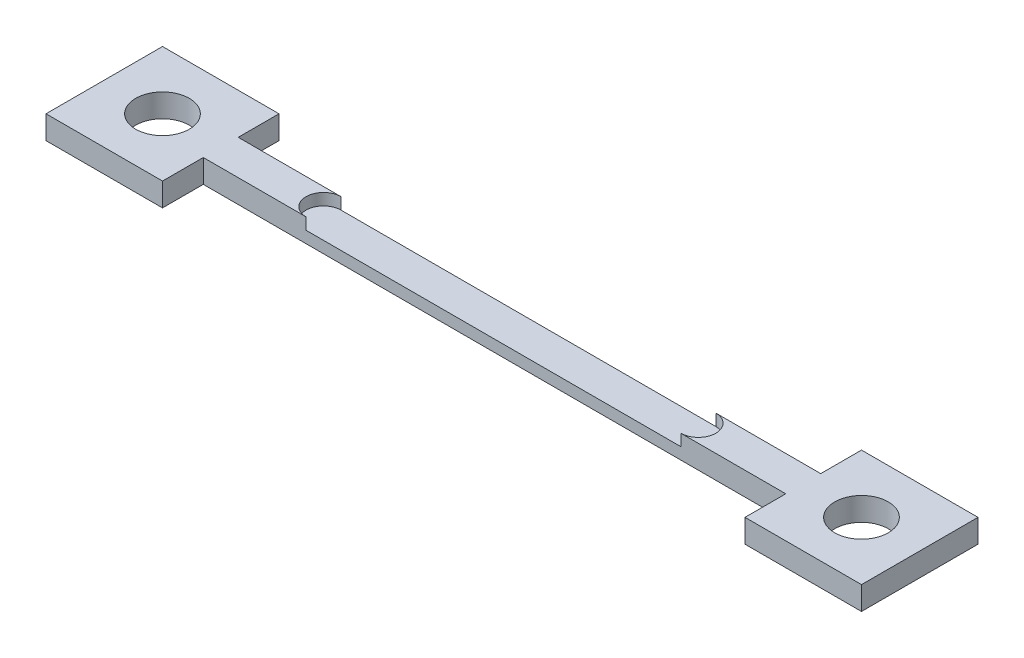
SolidWorks part; units mm, degrees
material "Commercially Pure CP-Ti UNS R50400 (SS)"
ref_plane "Front Plane" through (0, 0, 0) normal (0, 0, 1) x (1, 0, 0)
ref_plane "Top Plane" through (0, 0, 0) normal (0, 1, 0) x (1, 0, 0)
ref_plane "Right Plane" through (0, 0, 0) normal (1, 0, 0) x (0, 0, -1)
sketch "Sketch1" plane through (0, 0, 0) normal (0, 1, 0) x (1, 0, 0)
  line L0 (-41.424, -10.2833) -> (-41.424, -12.5058)
  line L1 (-47.774, -12.5058) -> (-41.424, -12.5058)
  line L2 (-47.774, -12.5058) -> (-47.774, -6.1558)
  line L3 (-47.774, -6.1558) -> (-41.424, -6.1558)
  line L4 (-3.324, -12.5058) -> (-3.324, -6.1558)
  line L7 (-41.424, -10.2833) -> (-9.674, -10.2833)
  line L9 (-41.424, -8.3783) -> (-9.674, -8.3783)
  line L13 (-41.424, -8.3783) -> (-41.424, -6.1558)
  line L14 (-9.674, -8.3783) -> (-9.674, -6.1558)
  line L15 (-9.674, -10.2833) -> (-9.674, -12.5058)
  line L16 (-9.674, -6.1558) -> (-3.324, -6.1558)
  line L17 (-9.674, -12.5058) -> (-3.324, -12.5058)
  point P0 (0, 0)
  point P6 (0, 0)
  dimension "D1" = 44.45
  dimension "D2" = 6.35
  dimension "D3" = 6.35
  dimension "D4" = 1.905
extrude "Boss-Extrude1" add sketch "Sketch1" along normal mid plane 1.27
hole_wizard "#97 (0.0059) Diameter Hole1" positions "Sketch4" profile "Sketch3" hole size "#97" standard "Ansi Inch" end condition through all
sketch "Sketch4" plane through (0, 0.635, 0) normal (0, 1, 0) x (-1, 0, 0)
  line L0 (47.774, 12.5058) -> (41.424, 6.1558) construction
  point P0 (44.599, 9.3308)
sketch "Sketch3" plane through (-44.599, 0.635, 9.3308) normal (1, 0, 0) x (0, 0, 1)
  line L0 (0, 0) -> (0, 1.27)
  line L1 (0, 1.27) -> (1.4605, 1.27)
  line L2 (1.4605, 1.27) -> (1.4605, 0)
  line L5 (1.4605, 0) -> (0, 0)
  line L11 (0, -6.35) -> (0, 107.95) construction
  dimension "Thru Hole Dia." = 2.921
  dimension "Thru Hole Depth" = 1.27
ref_plane "Plane1" [suppressed] through (-25.549, 0, 0) normal (1, 0, 0) x (0, 0, -1)
mirror "Mirror1" about plane through (-25.549, 0, 0) normal (1, 0, 0) of "#97 (0.0059) Diameter Hole1"
sketch "Sketch5" plane through (0, 0.635, 0) normal (0, 1, 0) x (1, 0, 0)
  line L1 (-25.549, -8.3783) -> (-15.3917, -8.3783)
  line L2 (-25.549, -8.3783) -> (-25.549, -10.2833)
  line L3 (-25.549, -10.2833) -> (-15.3917, -10.2833)
  line L4 (-15.3917, -8.3783) -> (-15.3917, -10.2833)
  line L5 (-9.674, -8.3783) -> (-41.424, -8.3783) construction
  line L6 (-41.424, -10.2833) -> (-9.674, -10.2833) construction
  line L8 (-25.549, -10.2833) -> (-35.8219, -10.2833)
  line L10 (-25.549, -8.3783) -> (-35.8219, -8.3783)
  line L11 (-35.8219, -10.2833) -> (-35.8219, -8.3783)
  circle A1 centre (-15.3917, -9.3308) radius 0.9525
  circle A2 centre (-35.8219, -9.3308) radius 0.9525
extrude "Cut-Extrude8" cut sketch "Sketch5" against normal blind 0.635
